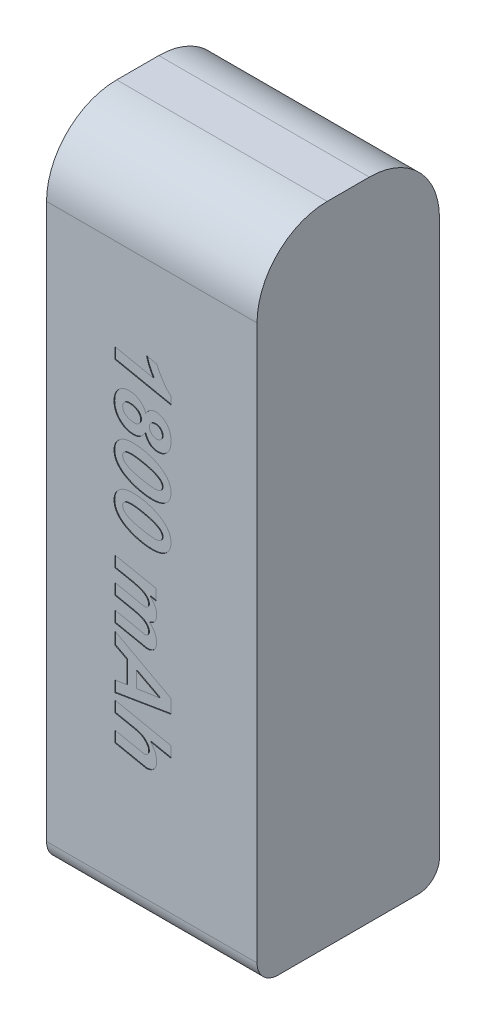
SolidWorks part; units mm, degrees
ref_plane "Спереди" through (0, 0, 0) normal (0, 0, 1) x (1, 0, 0)
ref_plane "Сверху" through (0, 0, 0) normal (0, 1, 0) x (1, 0, 0)
ref_plane "Справа" through (0, 0, 0) normal (1, 0, 0) x (0, 0, -1)
sketch "Sketch1" plane through (0, 0, 0) normal (0, 0, 1) x (1, 0, 0)
  line L1 (-15, 46) -> (15, 46)
  line L2 (-15, 46) -> (-15, -46)
  line L3 (-15, -46) -> (15, -46)
  line L4 (15, 46) -> (15, -46)
  line L5 (-15, 46) -> (15, -46) construction
  line L6 (-15, -46) -> (15, 46) construction
  point P0 (0, 0)
  dimension "D1" = 92
  dimension "D2" = 30
extrude "Boss-Extrude1" add sketch "Sketch1" along normal blind 26
fillet "Fillet1" radius 10 2 edges at (0, 46, 0) (0, 46, 26)
fillet "Fillet2" radius 3 2 edges at (0, -46, 0) (0, -46, 26)
sketch "Sketch2" plane through (0, 0, 26) normal (0, 0, 1) x (1, 0, 0)
  line L0 (-5.2774, 25.4231) -> (-5.2774, -30.7463) construction
  text T0 "<b><i>1800 mAh</i></b>" font "Arial" height in points 28
  point P3 (-8.3979, -30.7463)
  point P4 (-6.7458, 23.8628)
  point P5 (-5.2774, 25.4231)
extrude "Cut-Extrude1" cut sketch "Sketch2" against normal blind 0.1
